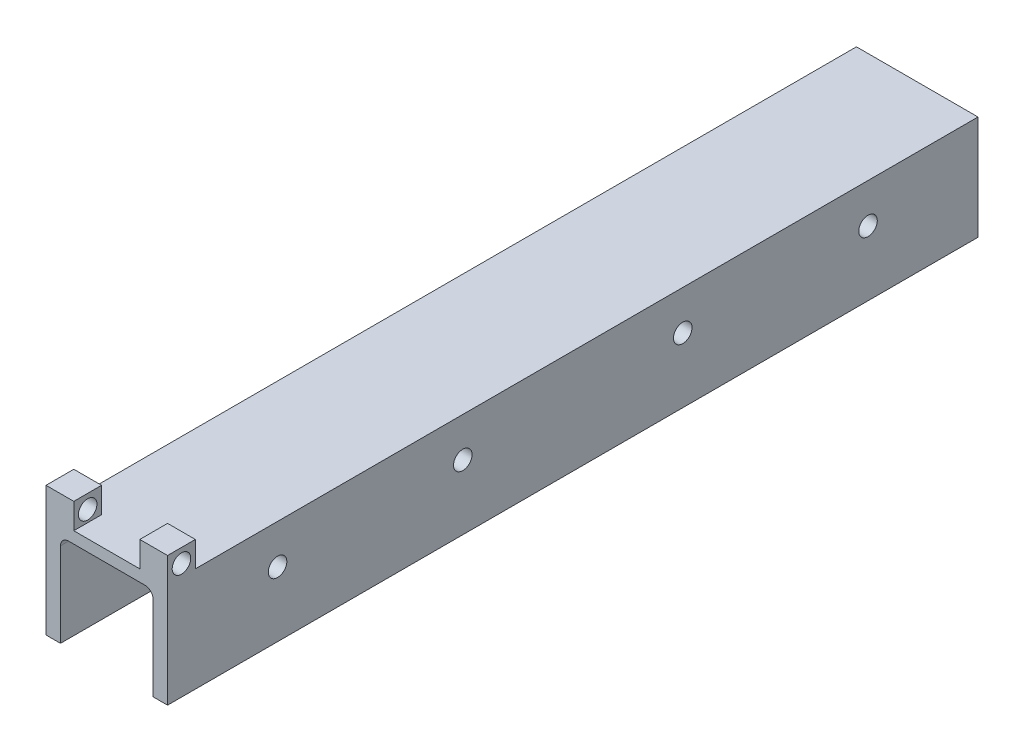
SolidWorks part; units mm, degrees
ref_plane "Front Plane" through (0, 0, 0) normal (0, 0, 1) x (1, 0, 0)
ref_plane "Top Plane" through (0, 0, 0) normal (0, 1, 0) x (1, 0, 0)
ref_plane "Right Plane" through (0, 0, 0) normal (1, 0, 0) x (0, 0, -1)
sketch "Sketch2" plane through (0, 0, 0) normal (0, 0, 1) x (1, 0, 0)
  line L0 (319.8414, 0) -> (-319.8414, 0) construction
  line L2 (0, 0) -> (0, 22.86)
  line L3 (0, 22.86) -> (26.67, 22.86)
  line L4 (26.67, 0) -> (26.67, 22.86)
  line L44 (23.495, 18.542) -> (23.495, 0)
  line L47 (3.175, 0) -> (3.175, 18.542)
  line L48 (4.953, 20.32) -> (21.717, 20.32)
  line L49 (0, 0) -> (3.175, 0)
  line L50 (23.495, 0) -> (26.67, 0)
  arc A0 (23.495, 18.542) -> (21.717, 20.32) centre (21.717, 18.542) ccw
  arc A1 (3.175, 18.542) -> (4.953, 20.32) centre (4.953, 18.542) cw
  point P15 (3.175, 20.32)
  point P16 (3.175, 20.32)
  dimension "D6" = 1.778
  dimension "D1" = 22.86
  dimension "D2" = 26.67
  dimension "D3" = 3.175
  dimension "D4" = 20.32
  dimension "D5" = 3.175
  dimension "D7" = 20.32
extrude "Boss-Extrude2" add sketch "Sketch2" against normal blind 177.8
sketch "Sketch19" plane through (0, 0, 0) normal (1, 0, 0) x (0, 0, -1)
  line L0 (0, 265.0009) -> (0, -265.0009) construction
  line L1 (319.8414, 0) -> (-319.8414, 0) construction
  line L3 (0, 0) -> (88.9, 0) construction
  line L4 (177.8, 0) -> (0, 0) construction
  line L5 (88.9, 0) -> (88.9, 22.86) construction
  line L6 (177.8, 22.86) -> (0, 22.86) construction
  line L7 (177.8, 0) -> (177.8, 22.86) construction
  circle A0 centre (24.13, 14.224) radius 2.032
  circle A1 centre (64.77, 14.224) radius 2.032
  circle A2 centre (113.03, 14.224) radius 2.032
  circle A3 centre (153.67, 14.224) radius 2.032
  dimension "D2" = 4.064
  dimension "D5" = 4.064
  dimension "D9" = 24.13
  dimension "D1" = 24.13
  dimension "D3" = 14.224
  dimension "D4" = 40.64
  dimension "D6" = 14.224
  dimension "D7" = 24.13
  dimension "D8" = 88.9
  dimension "D10" = 40.64
  dimension "D11" = 24.13
extrude "Cut-Extrude3" cut sketch "Sketch19" along normal through all
sketch "Sketch20" plane through (26.67, 0, 0) normal (1, 0, 0) x (0, 0, -1)
sketch "Sketch21" plane through (0, 22.86, 0) normal (0, 1, 0) x (1, 0, 0)
  line L0 (13.335, 0) -> (13.335, 177.8) construction
  line L1 (0, 0) -> (26.67, 0) construction
  line L2 (0, 0) -> (6.096, 0)
  line L3 (0, 0) -> (0, 6.096)
  line L4 (0, 6.096) -> (6.096, 6.096)
  line L5 (6.096, 0) -> (6.096, 6.096)
  line L6 (26.67, 177.8) -> (0, 177.8) construction
  line L7 (0, 0) -> (6.096, 0) construction
  line L8 (6.096, 0) -> (6.096, 6.5548) construction
  line L10 (20.574, 0) -> (20.574, 6.5548) construction
  line L11 (26.67, 0) -> (20.574, 0)
  line L12 (26.67, 0) -> (26.67, 6.096)
  line L13 (26.67, 6.096) -> (20.574, 6.096)
  line L14 (20.574, 0) -> (20.574, 6.096)
  dimension "D1" = 6.096
  dimension "D2" = 6.096
  dimension "D3" = 6.096
  dimension "D4" = 14.478
  dimension "D5" = 6.096
  dimension "D6" = 6.096
  dimension "D7" = 6.096
extrude "Boss-Extrude4" add sketch "Sketch21" along normal blind 5.588
sketch "Sketch22" plane through (20.574, 0, 0) normal (-1, 0, 0) x (0, 0, 1)
  line L0 (0, 28.448) -> (-6.096, 28.448) construction
  line L1 (0, -265.0009) -> (0, 265.0009) construction
  circle A0 centre (-3.048, 25.4) radius 2.032
  point P4 (-3.048, 28.448)
  dimension "D1" = 4.064
  dimension "D2" = 3.048
  dimension "D3" = 3.048
extrude "Cut-Extrude4" cut sketch "Sketch22" against normal through all both and the other way through all
